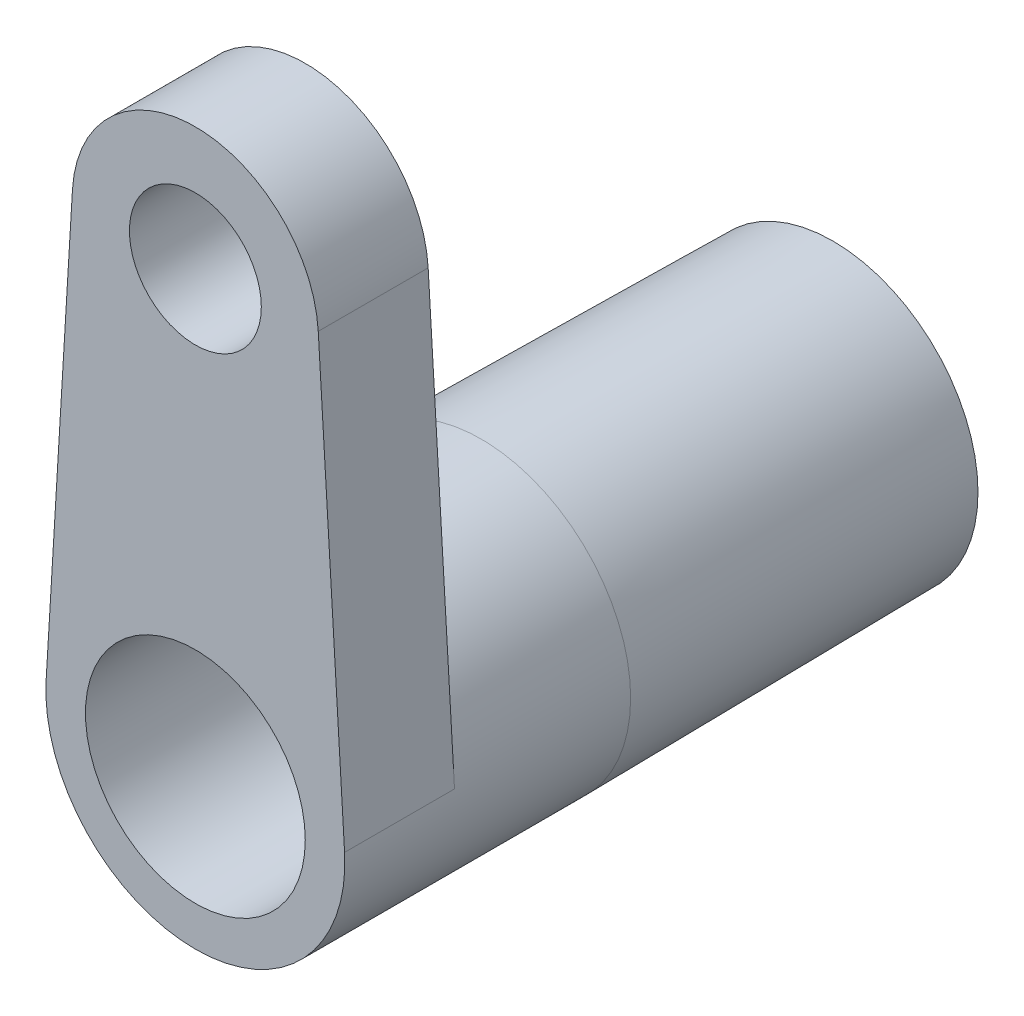
SolidWorks part; units mm, degrees
ref_plane "前视基准面" through (0, 0, 0) normal (0, 0, 1) x (1, 0, 0)
ref_plane "上视基准面" through (0, 0, 0) normal (0, 1, 0) x (1, 0, 0)
ref_plane "右视基准面" through (0, 0, 0) normal (1, 0, 0) x (0, 0, -1)
sketch "Sketch1" plane through (0, 0, 0) normal (0, 0, 1) x (1, 0, 0)
  circle A0 centre (0, 0) radius 2.4
  circle A1 centre (0, 0) radius 3.4
  dimension "D1" = 4.8
  dimension "D2" = 6.8
extrude "Boss-Extrude1" add sketch "Sketch1" along normal blind 3.5
sketch "Sketch2" plane through (0, 0, 3.5) normal (0, 0, 1) x (1, 0, 0)
  circle A0 centre (0, 0) radius 1.5
  circle A1 centre (0, 0) radius 3.4
  circle A2 centre (0, 0) radius 3.4
  dimension "D2" = 3
  dimension "D1" = 0
extrude "Boss-Extrude2" add sketch "Sketch2" along normal blind 8.5
sketch "Sketch3" plane through (0, 0, 12) normal (0, 0, 1) x (1, 0, 0)
  circle A0 centre (0, 0) radius 1.5 construction
  circle A1 centre (0, 0) radius 1.5
  circle A2 centre (0, 0) radius 2.5
  dimension "D1" = 5
extrude "Cut-Extrude1" cut sketch "Sketch3" against normal blind 6.5
sketch "Sketch4" plane through (0, 0, 12) normal (0, 0, 1) x (1, 0, 0)
  line L0 (-2.795, 10.168) -> (-3.3939, 0.204)
  line L2 (0, 0) -> (0, 3.0994) construction
  line L3 (2.795, 10.168) -> (3.3939, 0.204)
  circle A0 centre (0, 0) radius 3.4 construction
  arc A1 (-3.3939, 0.204) -> (3.3939, 0.204) centre (0, 0) ccw
  circle A2 centre (0, 10) radius 1.5
  arc A3 (-2.795, 10.168) -> (2.795, 10.168) centre (0, 10) cw
  circle A4 centre (0, 0) radius 2.5 construction
  circle A5 centre (0, 0) radius 2.5
  dimension "D1" = 3
  dimension "D3" = 2.8
  dimension "D2" = 10
extrude "Boss-Extrude3" add sketch "Sketch4" along normal blind 2.5
chamfer "倒角1" distance 0.1 distance2 8 1 edges at (3.4, 0, 0)
